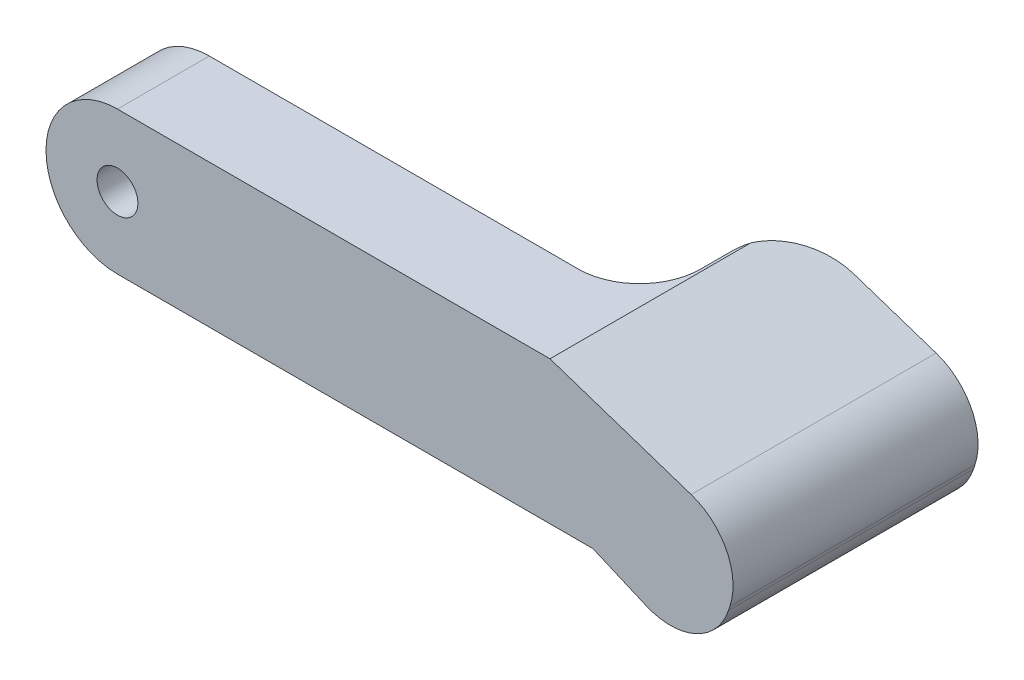
SolidWorks part; units mm, degrees
ref_plane "Plano frontal" through (0, 0, 0) normal (0, 0, 1) x (1, 0, 0)
ref_plane "Plano superior" through (0, 0, 0) normal (0, 1, 0) x (1, 0, 0)
ref_plane "Plano direito" through (0, 0, 0) normal (1, 0, 0) x (0, 0, -1)
sketch "Esboço1" plane through (0, 0, 0) normal (0, 0, 1) x (1, 0, 0)
  line L0 (0, 3.5) -> (21.1834, 3.5)
  line L1 (21.1834, 3.5) -> (30.9431, 0.2518)
  line L2 (30.9431, 0.2518) -> (28.8938, -5.9057)
  line L3 (28.8938, -5.9057) -> (23.2854, -3.5)
  line L4 (23.2854, -3.5) -> (0, -3.5)
  circle A0 centre (0, 0) radius 3.5
  dimension "D1" = 7
extrude "Ressalto-extrusão1" add sketch "Esboço1" along normal blind 12 contours A0 L4 L3 L2 L1 L0
sketch "Esboço2" plane through (0, 0, 0) normal (0, 0, -1) x (-1, 0, 0)
  line L1 (-21.0686, 7.8222) -> (6.289, 7.8222)
  line L2 (-21.0686, 7.8222) -> (-21.0686, -8.0968)
  line L3 (-21.0686, -8.0968) -> (6.289, -8.0968)
  line L4 (6.289, 7.8222) -> (6.289, -8.0968)
extrude "Corte-extrusão1" cut sketch "Esboço2" against normal blind 7.5
fillet "Filete1" radius 3 2 edges at (30.9431, 0.2518, 6) (28.8938, -5.9057, 6)
sketch "Esboço3" plane through (0, 0, 7.5) normal (0, 0, -1) x (-1, 0, 0)
  circle A0 centre (0, 0) radius 2.25
  dimension "D1" = 4.5
extrude "Corte-extrusão2" cut sketch "Esboço3" against normal blind 2.5
fillet "Filete2" radius 3 2 edges at (21.0686, 0, 7.5) (21.0686, 0, 0)
sketch "Esboço4" plane through (0, 0, 12) normal (0, 0, 1) x (1, 0, 0)
  circle A0 centre (0, 0) radius 1
  dimension "D1" = 2
extrude "Corte-extrusão3" cut sketch "Esboço4" against normal through all
